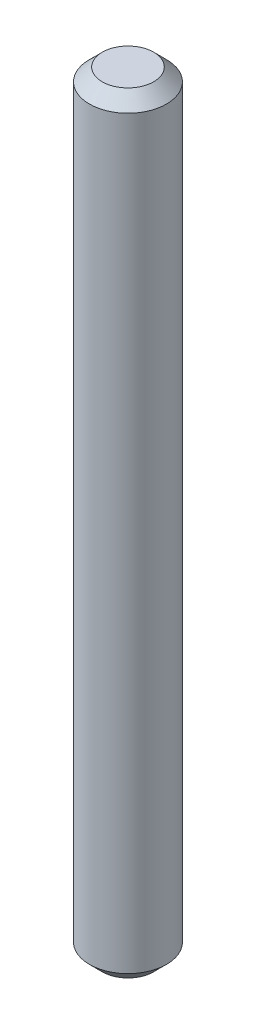
SolidWorks part; units mm, degrees
ref_plane "Front Plane" through (0, 0, 0) normal (0, 0, 1) x (1, 0, 0)
ref_plane "Top Plane" through (0, 0, 0) normal (0, 1, 0) x (1, 0, 0)
ref_plane "Right Plane" through (0, 0, 0) normal (1, 0, 0) x (0, 0, -1)
sketch "Sketch1" plane through (0, 0, 0) normal (0, 1, 0) x (1, 0, 0)
  circle A0 centre (0, 0) radius 1.5
  dimension "D1" = 3
extrude "Boss-Extrude1" add sketch "Sketch1" along normal blind 30
chamfer "Chamfer1" distance 0.5 angle 45 2 edges at (0, 0, 1.5) (0, 30, 1.5)
